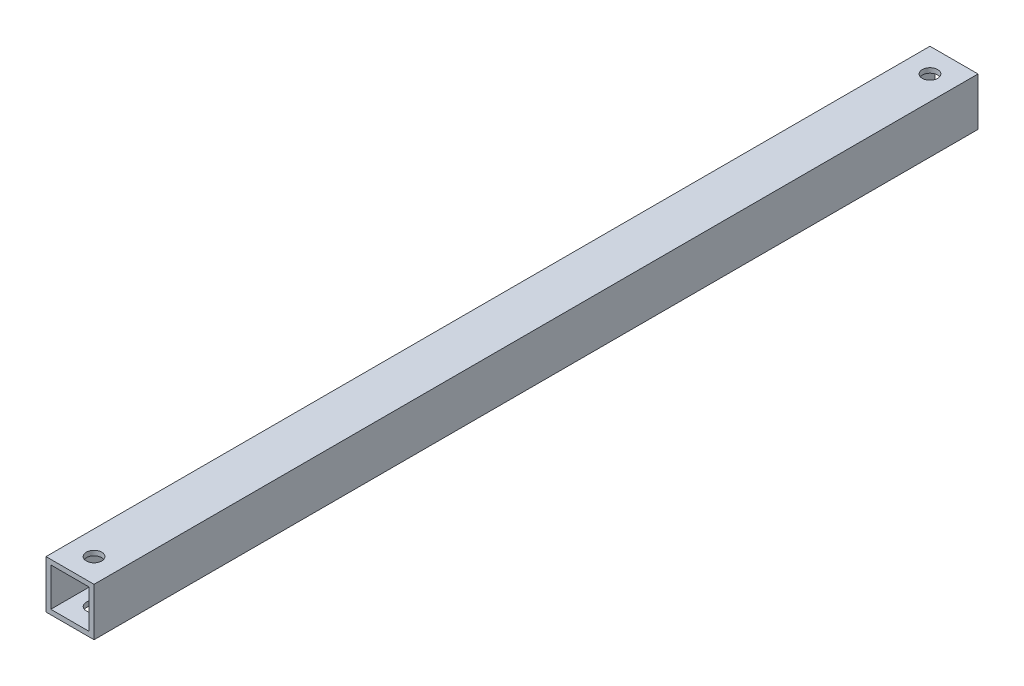
SolidWorks part; units mm, degrees
material "6061 合金"
ref_plane "正面" through (0, 0, 0) normal (0, 0, 1) x (1, 0, 0)
ref_plane "平面" through (0, 0, 0) normal (0, 1, 0) x (1, 0, 0)
ref_plane "右側面" through (0, 0, 0) normal (1, 0, 0) x (0, 0, -1)
sketch "断面 スケッチ" plane through (0, 0, 0) normal (0, 0, 1) x (1, 0, 0)
  line L1 (-5, -5) -> (5, -5)
  line L2 (-5, -5) -> (-5, 5)
  line L3 (-5, 5) -> (5, 5)
  line L4 (5, -5) -> (5, 5)
  line L5 (-5, -5) -> (5, 5) construction
  line L6 (-5, 5) -> (5, -5) construction
  point P0 (0, 0)
  dimension "D1" = 10
extrude "フレーム全長" add sketch "断面 スケッチ" along normal blind 184 thin thin type one direction reverse wall 1
sketch "上面穴 スケッチ" plane through (0, 5, 0) normal (0, 1, 0) x (1, 0, 0)
  line L0 (0, 0) -> (0, -184) construction
  line L1 (5, 0) -> (-5, 0) construction
  line L2 (5, -184) -> (-5, -184) construction
  line L3 (-5, -92) -> (5, -92) construction
  line L4 (-5, -184) -> (-5, 0) construction
  line L5 (5, -184) -> (5, 0) construction
  circle A0 centre (0, -5) radius 1.6
  circle A1 centre (0, -179) radius 1.6
  dimension "D1" = 5
  dimension "D2" = 3.2
sketch "側面穴 スケッチ" plane through (5, 0, 0) normal (1, 0, 0) x (0, 0, -1)
  line L0 (0, 0) -> (-184, 0) construction
  line L1 (0, -5) -> (0, 5) construction
  line L2 (-184, -5) -> (-184, 5) construction
  line L3 (-92, 5) -> (-92, -5) construction
  line L4 (-184, 5) -> (0, 5) construction
  line L5 (-184, -5) -> (0, -5) construction
  circle A0 centre (-15, 0) radius 1.6
  dimension "D1" = 15
  dimension "D2" = 3.2
extrude "上面穴貫通" cut sketch "上面穴 スケッチ" against normal through all
extrude "側面穴貫通" [suppressed] cut sketch "側面穴 スケッチ" against normal through all
fillet "フィレット" [suppressed] radius 5
